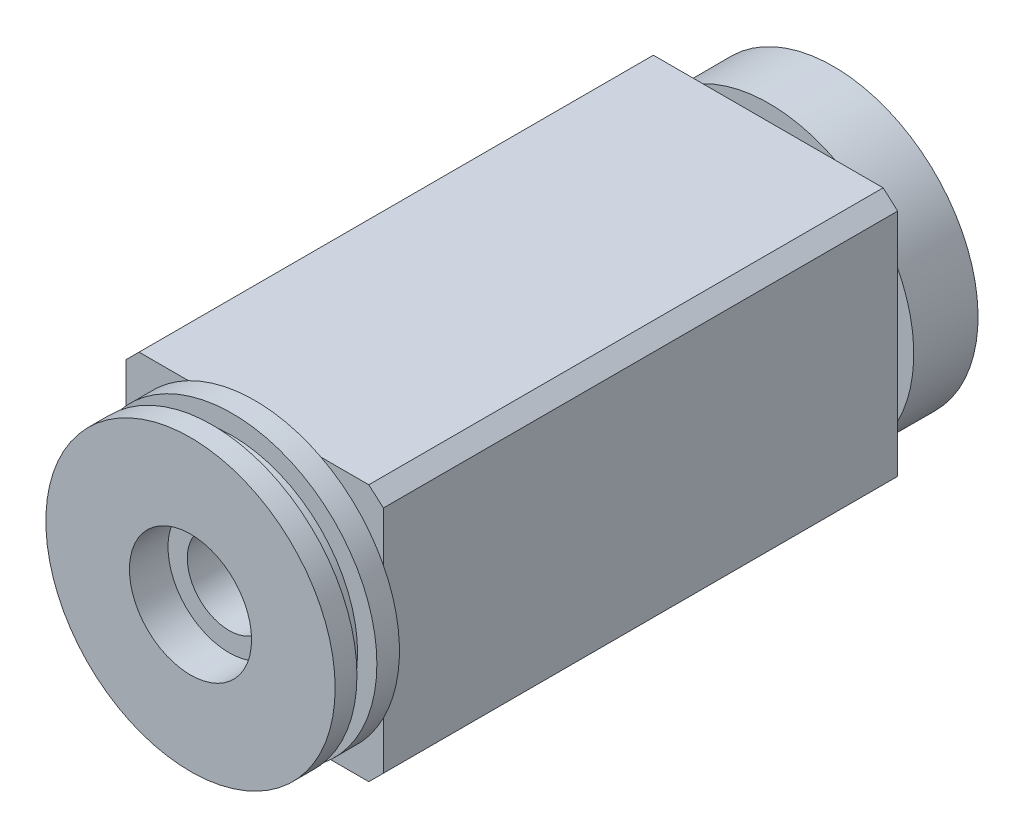
SolidWorks part; units mm, degrees
ref_plane "前视基准面" through (0, 0, 0) normal (0, 0, 1) x (1, 0, 0)
ref_plane "上视基准面" through (0, 0, 0) normal (0, 1, 0) x (1, 0, 0)
ref_plane "右视基准面" through (0, 0, 0) normal (1, 0, 0) x (0, 0, -1)
other "Configuration Table"
sketch "草图1" plane through (0, 0, 0) normal (0, 0, 1) x (1, 0, 0)
  line L0 (-20, 18) -> (-18, 20)
  line L1 (-18, 20) -> (17.7358, 20)
  line L2 (-20, 18) -> (-20, -18)
  line L3 (-18, -20) -> (17.7358, -20)
  line L4 (20, 18) -> (20, -17.7358)
  line L5 (17.7358, 20) -> (20, 18)
  line L6 (-18, -20) -> (-20, -18)
  line L7 (17.7358, -20) -> (20, -17.7358)
  dimension "D3" = 2
extrude "凸台-拉伸1" add sketch "草图1" along normal blind 80
sketch "草图3" plane through (0, 0, 80) normal (0, 0, 1) x (1, 0, 0)
  circle A0 centre (0, 0) radius 22.5
  dimension "D1" = 45
extrude "凸台-拉伸2" add sketch "草图3" along normal blind 10
sketch "草图4" plane through (0, 0, 0) normal (0, 0, -1) x (-1, 0, 0)
  circle A0 centre (0, 0) radius 22.5
  dimension "D1" = 45
extrude "凸台-拉伸3" add sketch "草图4" along normal blind 10
sketch "草图6" plane through (0, 0, -10) normal (0, 0, -1) x (-1, 0, 0)
  circle A0 centre (0, 0) radius 9.5
  dimension "D1" = 19
extrude "切除-拉伸3" cut sketch "草图6" against normal blind 6
sketch "草图7" plane through (0, 0, 90) normal (0, 0, 1) x (1, 0, 0)
  circle A0 centre (0, 0) radius 9.5
  dimension "D1" = 19
extrude "切除-拉伸4" cut sketch "草图7" against normal blind 6
sketch "草图8" plane through (0, 0, -10) normal (0, 0, -1) x (-1, 0, 0)
  circle A0 centre (0, 0) radius 6.5
  dimension "D1" = 13
extrude "切除-拉伸5" cut sketch "草图8" against normal blind 100
sketch "草图9" plane through (0, 0, 90) normal (0, 0, 1) x (1, 0, 0)
  circle A0 centre (0, 0) radius 22.5
  circle A1 centre (0, 0) radius 19.5
  dimension "D1" = 45
  dimension "D2" = 39
extrude "切除-拉伸7" cut sketch "草图9" against normal blind 3.1 from offset 3.39 offset against normal yes
